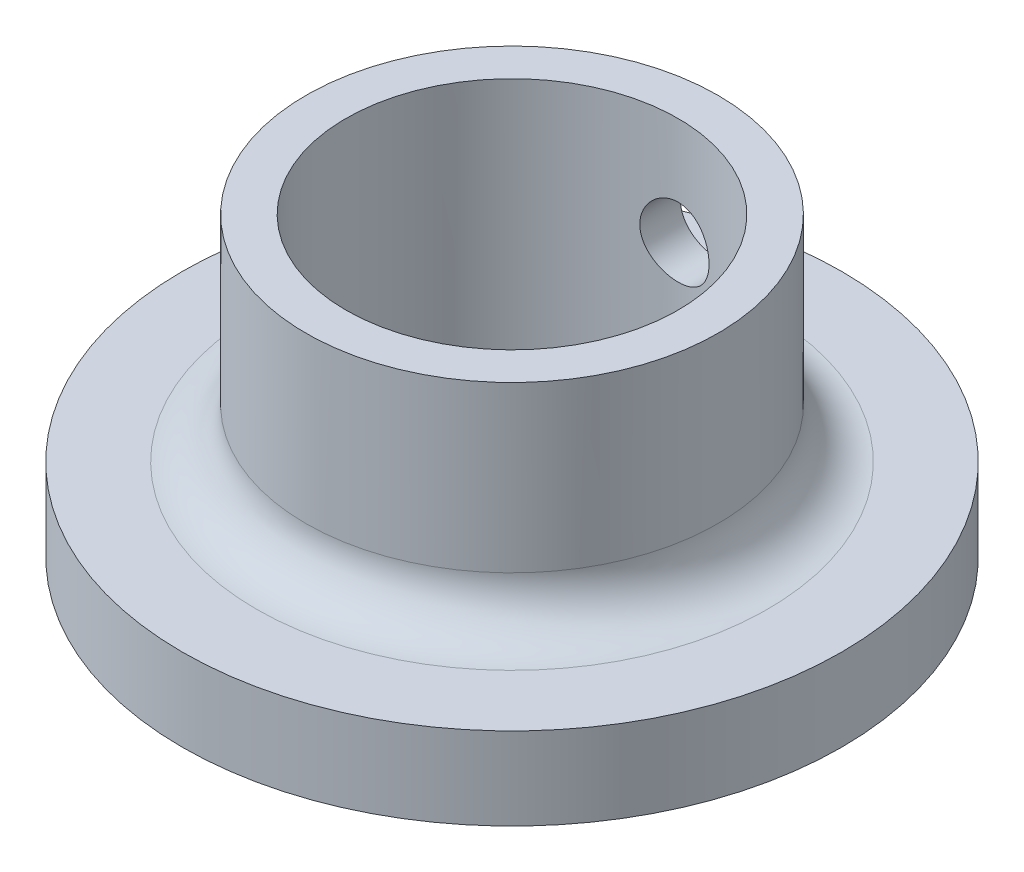
SolidWorks part; units mm, degrees
ref_plane "Ebene vorne" through (0, 0, 0) normal (0, 0, 1) x (1, 0, 0)
ref_plane "Ebene oben" through (0, 0, 0) normal (0, 1, 0) x (1, 0, 0)
ref_plane "Ebene rechts" through (0, 0, 0) normal (1, 0, 0) x (0, 0, -1)
sketch "Skizze2" plane through (0, 0, 0) normal (0, 0, 1) x (1, 0, 0)
  line L0 (0, 0) -> (0, 25.0943) construction
  line L1 (0, 0) -> (20, 0)
  line L2 (20, 0) -> (20, 5)
  line L3 (20, 5) -> (12.5, 5)
  line L4 (12.5, 5) -> (12.5, 18)
  line L5 (12.5, 18) -> (0, 18)
  line L6 (0, 18) -> (0, 0)
  dimension "D1" = 5
  dimension "D2" = 18
  dimension "D3" = 40
  dimension "D4" = 25
revolve "Rotation1" add sketch "Skizze2" angle 360 about L0
sketch "Skizze3" plane through (0, 18, 0) normal (0, 1, 0) x (1, 0, 0)
  circle A0 centre (0, 0) radius 10.075
  dimension "D1" = 20.15
extrude "Schnitt-Linear austragen1" cut sketch "Skizze3" against normal through all
sketch "Skizze4" plane through (0, 0, 0) normal (0, 0, 1) x (1, 0, 0)
  line L0 (0, -55) -> (0, 55) construction
  line L1 (12.5, 18) -> (-12.5, 18) construction
  circle A0 centre (0, 11.5) radius 2.1
  dimension "D2" = 4.2
  dimension "D1" = 6.5
extrude "Schnitt-Linear austragen2" cut sketch "Skizze4" against normal through all
fillet "Verrundung1" radius 3 1 edges at (0, 5, -12.5)
chamfer "Fase1" distance 2 angle 45 1 edges at (0, 0, 10.075)
